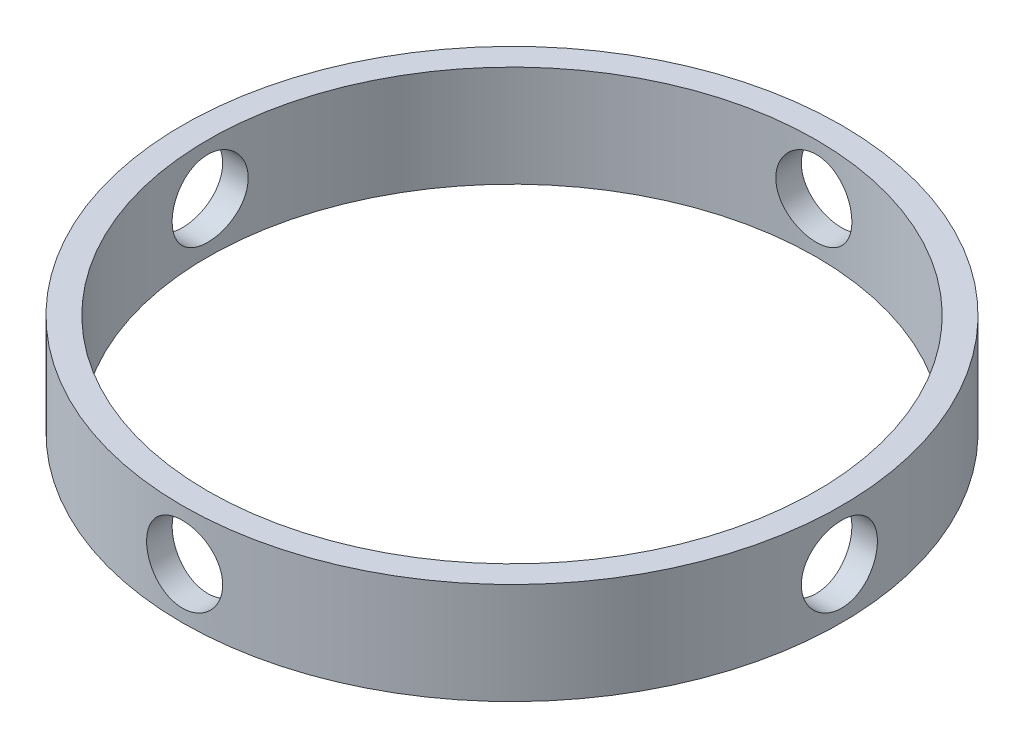
SolidWorks part; units mm, degrees
ref_plane "Front Plane" through (0, 0, 0) normal (0, 0, 1) x (1, 0, 0)
ref_plane "Top Plane" through (0, 0, 0) normal (0, 1, 0) x (1, 0, 0)
ref_plane "Right Plane" through (0, 0, 0) normal (1, 0, 0) x (0, 0, -1)
sketch "Sketch1" plane through (0, 0, 0) normal (0, 1, 0) x (1, 0, 0)
  circle A0 centre (0, 0) radius 65
  circle A1 centre (0, 0) radius 60
  dimension "D1" = 130
  dimension "D2" = 120
extrude "Boss-Extrude1" add sketch "Sketch1" along normal blind 20
sketch "Sketch2" plane through (0, 0, 0) normal (0, 0, 1) x (1, 0, 0)
  line L0 (-65, 20) -> (65, 0) construction
  line L1 (-65, 0) -> (65, 20) construction
  circle A0 centre (0, 10) radius 7.5
  dimension "D1" = 15
extrude "Cut-Extrude1" cut sketch "Sketch2" against normal through all and the other way through all
sketch "Sketch3" plane through (0, 0, 0) normal (1, 0, 0) x (0, 0, -1)
  line L0 (-65, 20) -> (65, 0) construction
  line L1 (65, 20) -> (-65, 0) construction
  circle A0 centre (0, 10) radius 7.5
  dimension "D1" = 15
extrude "Cut-Extrude2" cut sketch "Sketch3" against normal through all and the other way through all
